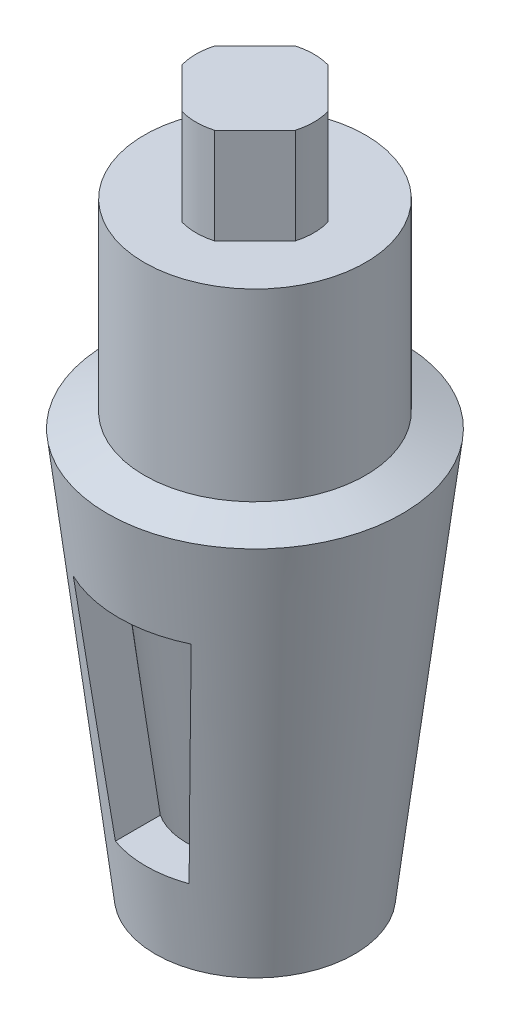
SolidWorks part; units mm, degrees
ref_plane "Front Plane" through (0, 0, 0) normal (0, 0, 1) x (1, 0, 0)
ref_plane "Top Plane" through (0, 0, 0) normal (0, 1, 0) x (1, 0, 0)
ref_plane "Right Plane" through (0, 0, 0) normal (1, 0, 0) x (0, 0, -1)
sketch "Sketch1" plane through (0, 0, 0) normal (0, 0, 1) x (1, 0, 0)
  line L0 (0, 293.1942) -> (0, -67.137) construction
  line L1 (0, 190) -> (16, 190)
  line L2 (16, 190) -> (16, 164)
  line L3 (16, 164) -> (30, 164)
  line L4 (30, 164) -> (30, 114)
  line L5 (30, 114) -> (40, 110)
  line L6 (40, 110) -> (27, 0)
  line L7 (27, 0) -> (16, 0)
  line L8 (0, 22) -> (10, 22)
  line L9 (0, 84) -> (16, 84)
  line L10 (16, 84) -> (10, 22)
  line L11 (0, 96) -> (27.3455, 96)
  line L12 (16, 0) -> (27.3455, 96)
  line L13 (20, 101) -> (22.3455, 101)
  line L14 (0, 157) -> (20, 157)
  line L15 (20, 157) -> (20, 101)
  line L16 (0, 190) -> (0, 157)
  arc A0 (27.3455, 96) -> (22.3455, 101) centre (22.3455, 96) ccw
  point P11 (21.5, 0)
  dimension "D12" = 16
  dimension "D16" = 5
  dimension "D1" = 16
  dimension "D2" = 26
  dimension "D3" = 50
  dimension "D4" = 110
  dimension "D5" = 4
  dimension "D6" = 80
  dimension "D7" = 60
  dimension "D8" = 16
  dimension "D9" = 22
  dimension "D10" = 62
  dimension "D11" = 10
  dimension "D13" = 12
  dimension "D14" = 27
  dimension "D15" = 5
  dimension "D17" = 56
  dimension "D18" = 40
revolve "Revolve1" add sketch "Sketch1" angle 360 about L0
sketch "Sketch3" plane through (0, 0, 0) normal (0, 0, 1) x (1, 0, 0)
  line L0 (16, 84) -> (-16, 84)
  line L1 (16, 84) -> (10, 22)
  line L2 (10, 22) -> (-10, 22)
  line L4 (0, 0) -> (0, 128.5787) construction
  line L5 (0, 293.1942) -> (0, -67.137) construction
  line L6 (-16, 84) -> (-10, 22)
  point P14 (0, 22)
  point P15 (0, 84)
extrude "Cut-Extrude1" cut sketch "Sketch3" against normal through all both and the other way through all
sketch "Sketch4" plane through (0, 190, 0) normal (0, 1, 0) x (1, 0, 0)
  line L0 (3.799, 16) -> (16, 3.799)
  line L2 (16, -3.799) -> (3.799, -16)
  line L3 (-3.799, -16) -> (-16, -3.799)
  line L4 (-16, 3.799) -> (-3.799, 16)
  line L6 (-3.799, 16) -> (3.799, 16)
  line L7 (-16, 3.799) -> (-16, -3.799)
  line L8 (-3.799, -16) -> (3.799, -16)
  line L9 (16, 3.799) -> (16, -3.799)
  line L10 (-9.8995, 9.8995) -> (9.8995, -9.8995) construction
  line L11 (-9.8995, -9.8995) -> (9.8995, 9.8995) construction
  point P2 (0, 16)
  point P3 (0, -16)
  point P4 (0, 0)
  point P11 (-16, 0)
  point P17 (16, 0)
  point P18 (0, 0)
  dimension "D1" = 32
  dimension "D2" = 32
  dimension "D3" = 28
  dimension "D4" = 7.598
  dimension "D5" = 7.598
extrude "Cut-Extrude2" cut sketch "Sketch4" against normal up to surface (26 mm away) flip side to cut up to face at (0, 164, 30)
